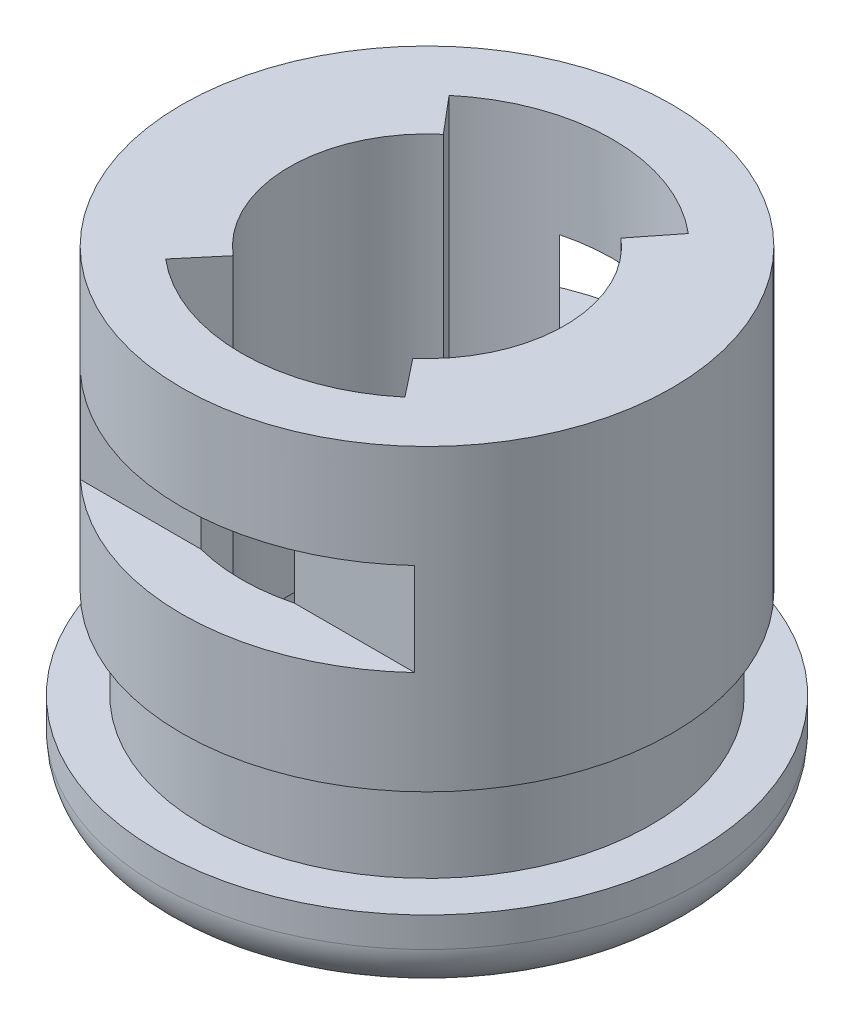
SolidWorks part; units mm, degrees
ref_plane "Alzado" through (0, 0, 0) normal (0, 0, 1) x (1, 0, 0)
ref_plane "Planta" through (0, 0, 0) normal (0, 1, 0) x (1, 0, 0)
ref_plane "Vista lateral" through (0, 0, 0) normal (1, 0, 0) x (0, 0, -1)
sketch "Croquis1" plane through (0, 0, 0) normal (0, 1, 0) x (1, 0, 0)
  circle A0 centre (0, 0) radius 4.5
  dimension "D1" = 9
extrude "Saliente-Extruir1" add sketch "Croquis1" along normal blind 1.3
sketch "Croquis2" plane through (0, 1.3, 0) normal (0, 1, 0) x (1, 0, 0)
  circle A0 centre (0, 0) radius 3.75
  dimension "D1" = 7.5
extrude "Saliente-Extruir2" add sketch "Croquis2" along normal blind 1.5
sketch "Croquis3" plane through (0, 2.8, 0) normal (0, 1, 0) x (1, 0, 0)
  circle A0 centre (0, 0) radius 4.1
  dimension "D1" = 8.2
extrude "Saliente-Extruir3" add sketch "Croquis3" along normal blind 5
sketch "Croquis4" plane through (0, 7.8, 0) normal (0, 1, 0) x (1, 0, 0)
  line L0 (-2, 2.3685) -> (-1.4839, 1.7573)
  line L1 (2, 2.3685) -> (1.5037, 1.7404)
  line L2 (0, 4.9014) -> (0, 0) construction
  line L3 (-5.0276, 0) -> (-2.4, 0) construction
  line L4 (0, 0) -> (0, -5.1811) construction
  line L5 (2.3, 0) -> (5.7603, 0) construction
  line L7 (2, -2.3685) -> (1.5037, -1.7404)
  line L8 (-2, -2.3685) -> (-1.4839, -1.7573)
  line L9 (-2.4, 0) -> (2.3, 0) construction
  arc A0 (-2, -2.3685) -> (2, -2.3685) centre (0, 0) ccw
  arc A1 (-1.4839, 1.7573) -> (-1.4839, -1.7573) centre (0, 0) ccw
  arc A2 (1.5037, -1.7404) -> (1.5037, 1.7404) centre (0, 0) ccw
  arc A3 (2, 2.3685) -> (-2, 2.3685) centre (0, 0) ccw
  dimension "D1" = 6.2
  dimension "D2" = 4.6
  dimension "D3" = 4
  dimension "D4" = 78.492
  dimension "D5" = 2
extrude "Cortar-Extruir3" cut sketch "Croquis4" against normal blind 6.2
sketch "Croquis7" plane through (0, 1.6, 0) normal (0, 1, 0) x (1, 0, 0)
  line L0 (1.6424, 1.75) -> (1.6424, -1.75)
  line L1 (-5.5274, 0) -> (7.1755, 0) construction
  line L2 (-0.6, 3.1) -> (-0.6, 2.3238)
  line L3 (-0.6, -3.1) -> (0.6, -3.1)
  line L4 (0.6, -3.1) -> (0.6, -2.3238)
  line L5 (0.6, 3.1) -> (-0.6, 3.1)
  line L6 (-0.6, -2.3238) -> (-0.6, -3.1)
  line L7 (0.6, 2.3238) -> (0.6, 3.1)
  arc A0 (1.6424, 1.75) -> (0.6, 2.3238) centre (0, 0) ccw
  arc A4 (0.6, -2.3238) -> (1.6424, -1.75) centre (0, 0) ccw
  arc A5 (-0.6, 2.3238) -> (-0.6, -2.3238) centre (0, 0) ccw
  point P2 (0, 0)
  point P8 (0, 0)
  point P12 (0.219, 0.8296)
  dimension "D1" = 4.8
  dimension "D3" = 6.2
  dimension "D2" = 3.5
  dimension "D4" = 0.6
  dimension "D5" = 1.2
  dimension "D6" = 3.1
extrude "Cortar-Extruir4" cut sketch "Croquis7" against normal blind 1.8 contours A0 L7 L5 L2 A5 L6 L3 L4 A4 L0
fillet "Redondeo1" radius 0.8 1 edges at (0, 0, 4.5)
sketch "Croquis8" plane through (0, 0, 0) normal (1, 0, 0) x (0, 0, -1)
  line L0 (-4.1, 7.8) -> (-4.1, 2.8) construction
  line L1 (-4.1, 6.075) -> (-3, 6.075)
  line L2 (-4.1, 6.075) -> (-4.1, 4.525)
  line L3 (-4.1, 4.525) -> (-3, 4.525)
  line L4 (-3, 6.075) -> (-3, 4.525)
  line L5 (-4.1, 2.8) -> (4.1, 2.8) construction
  line L6 (0, 55) -> (0, -55) construction
  line L7 (3, 6.075) -> (3, 4.525)
  line L8 (4.1, 4.525) -> (3, 4.525)
  line L9 (4.1, 6.075) -> (4.1, 4.525)
  line L10 (4.1, 6.075) -> (3, 6.075)
  point P6 (-4.1, 5.3)
  dimension "D1" = 1.1
  dimension "D2" = 2.5
  dimension "D3" = 1.55
extrude "Cortar-Extruir5" cut sketch "Croquis8" against normal through all both and the other way through all
